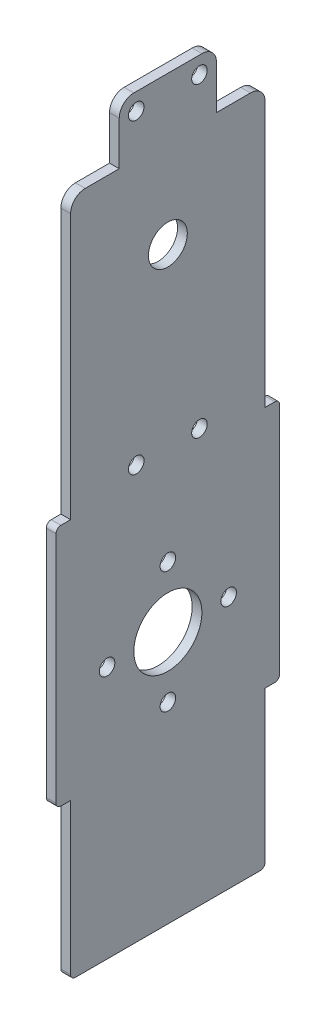
SolidWorks part; units mm, degrees
ref_plane "前视基准面" through (0, 0, 0) normal (0, 0, 1) x (1, 0, 0)
ref_plane "上视基准面" through (0, 0, 0) normal (0, 1, 0) x (1, 0, 0)
ref_plane "右视基准面" through (0, 0, 0) normal (1, 0, 0) x (0, 0, -1)
sketch "草图1" plane through (0, 0, 0) normal (1, 0, 0) x (0, 0, -1)
  line L1 (-20, -69.75) -> (20, -69.75)
  line L2 (-20, -69.75) -> (-20, 69.75)
  line L3 (-20, 69.75) -> (20, 69.75)
  line L4 (20, -69.75) -> (20, 69.75)
  line L5 (-20, -69.75) -> (20, 69.75) construction
  line L6 (-20, 69.75) -> (20, -69.75) construction
  line L7 (-10, 81.75) -> (10, 81.75)
  line L8 (-10, 81.75) -> (-10, 69.75)
  line L9 (-10, 69.75) -> (10, 69.75)
  line L10 (10, 81.75) -> (10, 69.75)
  line L11 (20, 12.25) -> (23, 12.25)
  line L12 (20, 12.25) -> (20, -37.75)
  line L13 (20, -37.75) -> (23, -37.75)
  line L14 (23, 12.25) -> (23, -37.75)
  line L15 (-20, 12.25) -> (-23, 12.25)
  line L16 (-20, 12.25) -> (-20, -37.75)
  line L17 (-20, -37.75) -> (-23, -37.75)
  line L18 (-23, 12.25) -> (-23, -37.75)
  circle A0 centre (0, -17.75) radius 7
  circle A1 centre (0, -17.75) radius 12.5
  circle A2 centre (0, -5.25) radius 1.6
  circle A3 centre (12.5, -17.75) radius 1.6
  circle A4 centre (0, -30.25) radius 1.6
  circle A5 centre (-12.5, -17.75) radius 1.6
  circle A6 centre (-6.5, 15.25) radius 1.6
  circle A7 centre (6.5, 15.25) radius 1.6
  circle A8 centre (-6.5, 78.25) radius 1.6
  circle A9 centre (6.5, 78.25) radius 1.6
  circle A10 centre (0, 51.25) radius 4
  point P0 (0, 0)
  dimension "D8" = 13.5
  dimension "D10" = 33
  dimension "D15" = 32
  dimension "D1" = 139.5
  dimension "D2" = 40
  dimension "D3" = 10
  dimension "D4" = 10
  dimension "D5" = 20
  dimension "D6" = 12
  dimension "D7" = 52
  dimension "D9" = 13.5
  dimension "D11" = 33
  dimension "D12" = 63
  dimension "D13" = 63
  dimension "D14" = 69
  dimension "D16" = 32
  dimension "D17" = 50
  dimension "D18" = 50
  dimension "D19" = 3
  dimension "D20" = 3
extrude "凸台-拉伸1" add sketch "草图1" along normal blind 2 contours L1 L4 L3 L2 A10 A7 A6 A5 A1 A2 A3 A4 | L10 L7 L8 L3 A9 A8 | A5 A1 A4 A3 A2 A0 | L14 L11 L4 L13 | L15 L18 L17 L2
fillet "圆角1" radius 3 4 edges at (1, 81.75, 10) (1, 81.75, -10) (1, 69.75, -20) (1, 69.75, 20)
fillet "圆角2" radius 1 6 edges at (1, -69.75, -20) (1, -69.75, 20) (1, 12.25, -23) (1, -37.75, -23) (1, -37.75, 23) (1, 12.25, 23)
